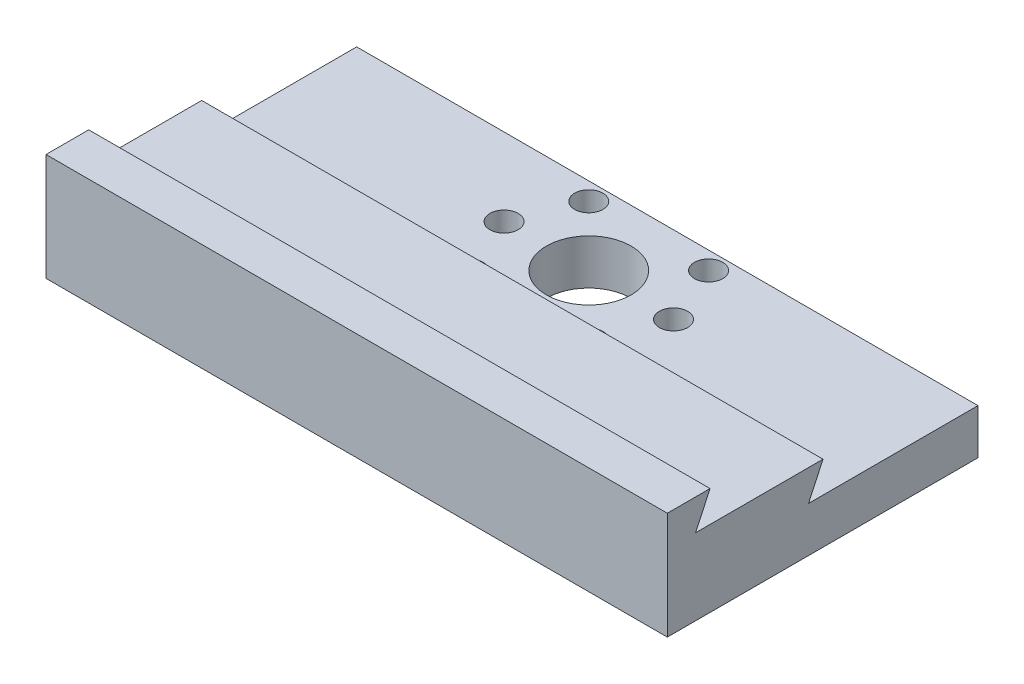
SolidWorks part; units mm, degrees
material "6061 Alloy"
ref_plane "Front Plane" through (0, 0, 0) normal (0, 0, 1) x (1, 0, 0)
ref_plane "Top Plane" through (0, 0, 0) normal (0, 1, 0) x (1, 0, 0)
ref_plane "Right Plane" through (0, 0, 0) normal (1, 0, 0) x (0, 0, -1)
sketch "Sketch1" plane through (0, 0, 0) normal (1, 0, 0) x (0, 0, -1)
  line L0 (0, 0) -> (0, 19)
  line L1 (0, 19) -> (7.5647, 19)
  line L2 (7.5647, 19) -> (5, 13.5)
  line L3 (5, 13.5) -> (27.5647, 13.5)
  line L4 (27.5647, 13.5) -> (25, 8)
  line L5 (25, 8) -> (55, 8)
  line L6 (55, 8) -> (55, 0)
  line L7 (55, 0) -> (0, 0)
  dimension "D1" = 65
  dimension "D2" = 65
  dimension "D3" = 5.5
  dimension "D4" = 5.5
  dimension "D5" = 8
  dimension "D6" = 30
  dimension "D7" = 50
  dimension "D8" = 5
extrude "Boss-Extrude1" add sketch "Sketch1" along normal blind 110
sketch "Sketch2" plane through (0, 0, -55) normal (0, 0, -1) x (-1, 0, 0)
  line L0 (-55, 8) -> (-55, 0) construction
  line L1 (-110, 8) -> (0, 8) construction
  line L2 (-110, 0) -> (0, 0) construction
  line L3 (-40.9488, 4.5) -> (-20.9488, 4.5) construction
  circle A0 centre (-20.9488, 4.5) radius 2
  circle A1 centre (-89.0512, 4.5) radius 2
  point P11 (-20.9488, 4.5)
  dimension "D1" = 4
  dimension "D3" = 3.5
  dimension "D2" = 20
extrude "M$_DRILL" cut sketch "Sketch2" against normal blind 20
sketch "Sketch6" plane through (0, 8, 0) normal (0, 1, 0) x (1, 0, 0)
  line L1 (0, 25) -> (0, 60.0537)
  circle A0 centre (54.8296, 41.2603) radius 7.5
  point P2 (54.8296, 43.3055)
  point P4 (0, 0)
  point P9 (54.8296, 41.2603)
extrude "Cut-Extrude2" cut sketch "Sketch6" against normal blind 10 contours A0
sketch "Sketch7" plane through (0, 8, 0) normal (0, 1, 0) x (1, 0, 0)
  circle A0 centre (54.8296, 41.2603) radius 15
  point P3 (32.4984, 37.3605)
  point P4 (32.4984, 37.3605)
sketch "Sketch8" plane through (0, 8, 0) normal (0, 1, 0) x (1, 0, 0)
  circle A0 centre (39.8296, 41.2603) radius 2.505
  circle A1 centre (54.8296, 41.2603) radius 15 construction
  point P4 (40, 40)
  point P5 (0, 0)
  point P6 (39.8296, 41.2603)
extrude "Cut-Extrude3" cut sketch "Sketch8" against normal blind 10
pattern_circular "CirPattern1" count 8 over 360 about axis through (54.8296, 0, -41.2603) along (0, 1, 0) skipping 2, 6 of "Cut-Extrude3"
